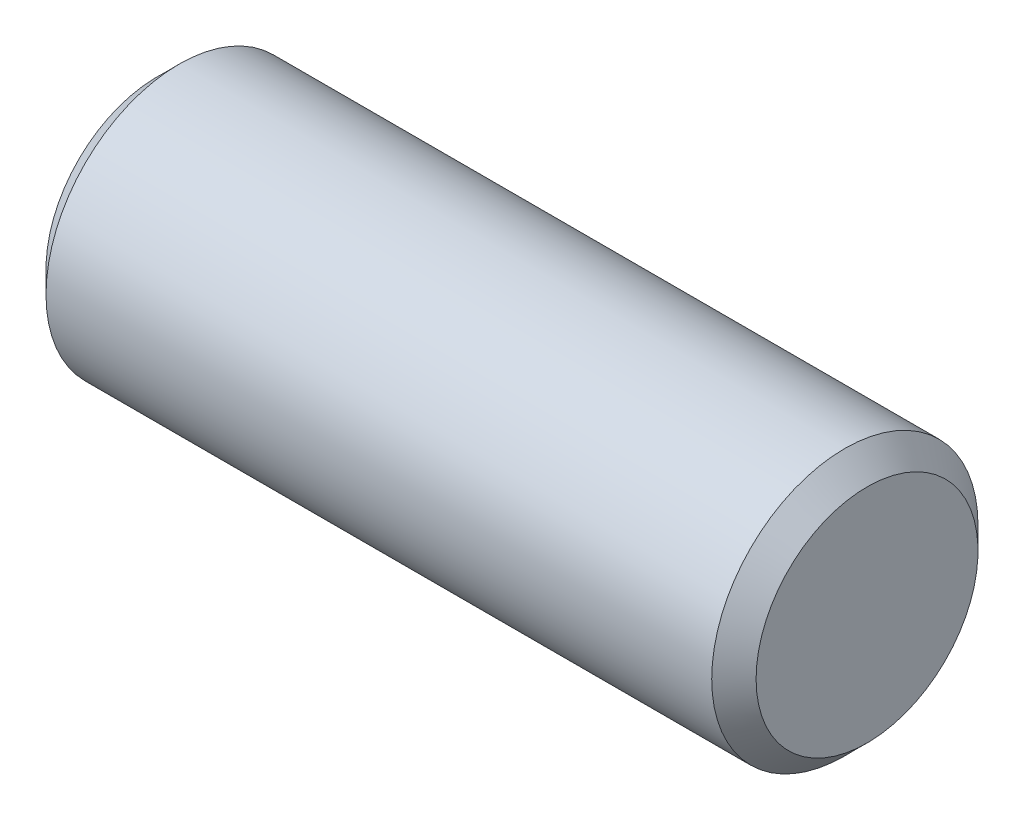
SolidWorks part; units mm, degrees
ref_plane "Front Plane" through (0, 0, 0) normal (0, 0, 1) x (1, 0, 0)
ref_plane "Top Plane" through (0, 0, 0) normal (0, 1, 0) x (1, 0, 0)
ref_plane "Right Plane" through (0, 0, 0) normal (1, 0, 0) x (0, 0, -1)
sketch "Sketch1" plane through (0, 0, 0) normal (1, 0, 0) x (0, 0, -1)
  circle A0 centre (0, 0) radius 4.7625
  dimension "D1" = 9.525
extrude "Boss-Extrude1" add sketch "Sketch1" along normal blind 25.4
chamfer "Chamfer1" distance 0.7937 angle 45 2 edges at (25.4, 0, -4.7625) (0, 0, -4.7625)
